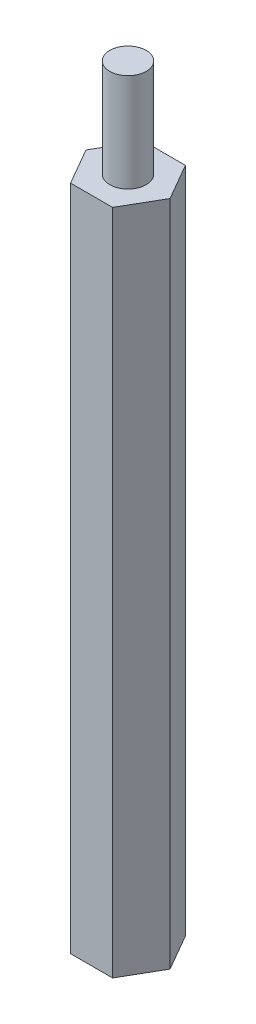
SolidWorks part; units mm, degrees
ref_plane "Front Plane" through (0, 0, 0) normal (0, 0, 1) x (1, 0, 0)
ref_plane "Top Plane" through (0, 0, 0) normal (0, 1, 0) x (1, 0, 0)
ref_plane "Right Plane" through (0, 0, 0) normal (1, 0, 0) x (0, 0, -1)
sketch "Sketch3" plane through (0, 0, 0) normal (0, 1, 0) x (1, 0, 0)
  line L1 (-3.4641, 0) -> (-1.7321, -3)
  line L2 (-1.7321, -3) -> (1.7321, -3)
  line L3 (1.7321, -3) -> (3.4641, 0)
  line L4 (3.4641, 0) -> (1.7321, 3)
  line L5 (1.7321, 3) -> (-1.7321, 3)
  line L6 (-1.7321, 3) -> (-3.4641, 0)
  circle A0 centre (0, 0) radius 3 construction
  dimension "D1" = 6
extrude "Boss-Extrude1" add sketch "Sketch3" along normal blind 55
sketch "Sketch5" plane through (0, 55, 0) normal (0, 1, 0) x (1, 0, 0)
  circle A0 centre (0, 0) radius 1.5
  dimension "D1" = 3
extrude "Boss-Extrude2" add sketch "Sketch5" along normal blind 8.0916
sketch "Sketch6" plane through (0, 0, 0) normal (0, -1, 0) x (1, 0, 0)
  circle A0 centre (0, 0) radius 1.5
extrude "Cut-Extrude1" cut sketch "Sketch6" against normal blind 4
